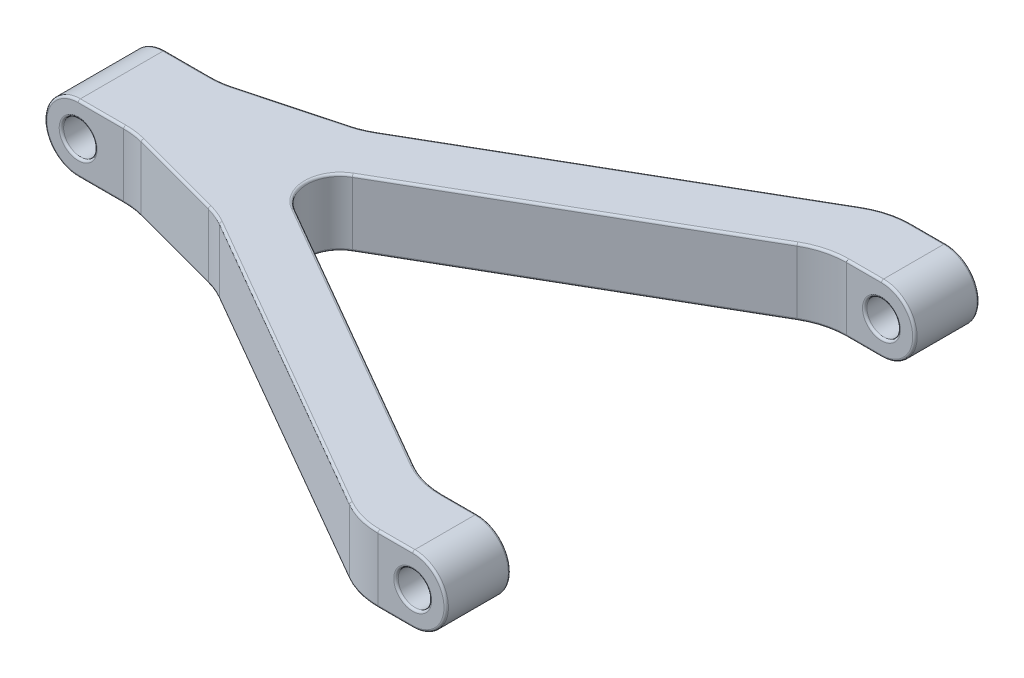
SolidWorks part; units mm, degrees
ref_plane "Front Plane" through (0, 0, 0) normal (0, 0, 1) x (1, 0, 0)
ref_plane "Top Plane" through (0, 0, 0) normal (0, 1, 0) x (1, 0, 0)
ref_plane "Right Plane" through (0, 0, 0) normal (1, 0, 0) x (0, 0, -1)
sketch "Sketch1" plane through (0, 0, 0) normal (0, 1, 0) x (1, 0, 0)
  line L0 (0, 0) -> (-138.9524, 0) construction
  line L1 (-138.9524, -39) -> (-138.9524, 39)
  line L2 (-138.9524, 39) -> (-88.9524, 39)
  line L3 (-88.9524, 39) -> (11.0476, 65.7949)
  line L4 (11.0476, 65.7949) -> (311.0476, 239)
  line L5 (311.0476, 239) -> (361.0476, 239)
  line L6 (311.0476, -239) -> (361.0476, -239)
  line L7 (11.0476, -65.7949) -> (311.0476, -239)
  line L8 (-88.9524, -39) -> (11.0476, -65.7949)
  line L9 (-138.9524, -39) -> (-88.9524, -39)
  line L10 (361.0476, 239) -> (361.0476, 181.26)
  line L11 (361.0476, 181.26) -> (311.039, 181.26)
  line L12 (311.039, 181.26) -> (42.0875, 25.9808)
  line L13 (42.0875, -25.9808) -> (311.039, -181.26)
  line L14 (311.039, -181.26) -> (361.0476, -181.26)
  line L15 (361.0476, -181.26) -> (361.0476, -239)
  arc A0 (42.0875, -25.9808) -> (42.0875, 25.9808) centre (57.0875, 0) cw
  point P20 (-2.9125, 0)
  dimension "D12" = 30
  dimension "D2" = 100
  dimension "D3" = 300
  dimension "D4" = 500
  dimension "D5" = 165
  dimension "D6" = 165
  dimension "D7" = 50
  dimension "D8" = 57.74
  dimension "D9" = 50
  dimension "D10" = 362.52
  dimension "D11" = 39
extrude "Boss-Extrude1" add sketch "Sketch1" along normal blind 60
sketch "Sketch2" plane through (0, 0, 0) normal (0, 0, 1) x (1, 0, 0)
  line L0 (-138.9524, 60) -> (-138.9524, 0) construction
  line L1 (-138.9524, 60) -> (-88.9524, 60) construction
  line L2 (-138.9524, 0) -> (-88.9524, 0) construction
  line L3 (-138.9524, 60) -> (-138.9524, 0)
  arc A0 (-138.9524, 60) -> (-138.9524, 0) centre (-138.9524, 30) ccw
extrude "Boss-Extrude2" add sketch "Sketch2" along normal up to vertex and the other way up to vertex
sketch "Sketch3" plane through (0, 0, 39) normal (0, 0, 1) x (1, 0, 0)
  circle A0 centre (-138.9524, 30) radius 15
  dimension "D1" = 30
extrude "Cut-Extrude1" cut sketch "Sketch3" against normal through all both and the other way through all
sketch "Sketch5" plane through (0, 0, 239) normal (0, 0, 1) x (1, 0, 0)
  line L0 (361.0476, 60) -> (361.0476, 0) construction
  line L1 (311.0476, 60) -> (361.0476, 60) construction
  line L2 (311.0476, 0) -> (361.0476, 0) construction
  circle A0 centre (361.0476, 30) radius 30
extrude "Boss-Extrude4" add sketch "Sketch5" against normal up to surface (57.74 mm away) up to face at (336.0433, 30, 181.26)
sketch "Sketch6" plane through (0, 0, 239) normal (0, 0, 1) x (1, 0, 0)
  circle A0 centre (361.0476, 30) radius 15
  dimension "D1" = 30
extrude "Cut-Extrude2" cut sketch "Sketch6" against normal blind 77.47 and the other way through all
mirror "Mirror2" about plane through (0, 0, 0) normal (0, 0, 1) of "Boss-Extrude1", "Cut-Extrude2", "Boss-Extrude4"
sketch "Sketch7" plane through (0, 0, 239) normal (0, 0, 1) x (1, 0, 0)
  line L0 (361.0476, 45) -> (361.0476, 15) construction
  circle A0 centre (361.0476, 30) radius 15
  circle A1 centre (-138.9524, 30) radius 15
extrude "Cut-Extrude3" cut sketch "Sketch7" against normal through all and the other way through all
fillet "Fillet1" radius 70 8 edges at (-88.9524, 30, -39) (11.0476, 30, -65.7949) (311.039, 30, -181.26) (311.0476, 30, -239) (311.039, 30, 181.26) (311.0476, 30, 239) (11.0476, 30, 65.7949) (-88.9524, 30, 39)
fillet "Fillet18" radius 2 53 edges at (-168.9524, 30, -39) (-168.9524, 30, 39) (-118.5602, 60, 39) (-89.0312, 60, 39.5989) (-38.9524, 60, 52.3975) (10.8165, 60, 66.353) (156.9163, 60, 150.0123) (311.6867, 60, 236.6148) (345.4258, 60, 239) (391.0476, 30, 181.26) (391.0476, 30, 239) (345.4215, 60, 181.26) (311.6781, 60, 178.8748) (168.4415, 60, 98.9313) (27.0875, 60, 0) (168.4415, 60, -98.9313) (311.6781, 60, -178.8748) (345.4215, 60, -181.26) (391.0476, 30, -239) (391.0476, 30, -181.26) (345.4258, 60, -239) (311.6867, 60, -236.6148) (156.9163, 60, -150.0123) (10.8165, 60, -66.353) (-38.9524, 60, -52.3975) (-89.0312, 60, -39.5989) (-118.5602, 60, -39) (346.0476, 30, 239) (10.8165, 0, -66.353) (-38.9524, 0, -52.3975) (-89.0312, 0, -39.5989) (-118.5602, 0, -39) (-118.5602, 0, 39) (-89.0312, 0, 39.5989) (-38.9524, 0, 52.3975) (10.8165, 0, 66.353) (156.9163, 0, 150.0123) (311.6867, 0, 236.6148) (345.4258, 0, 239) (345.4215, 0, 181.26) (311.6781, 0, 178.8748) (168.4415, 0, 98.9313) (27.0875, 0, 0) (168.4415, 0, -98.9313) (311.6781, 0, -178.8748) (345.4215, 0, -181.26) (345.4258, 0, -239) (311.6867, 0, -236.6148) (156.9163, 0, -150.0123) (-153.9524, 30, 39) (-123.9524, 30, -39) (376.0476, 30, -239) (346.0476, 30, -181.26)
